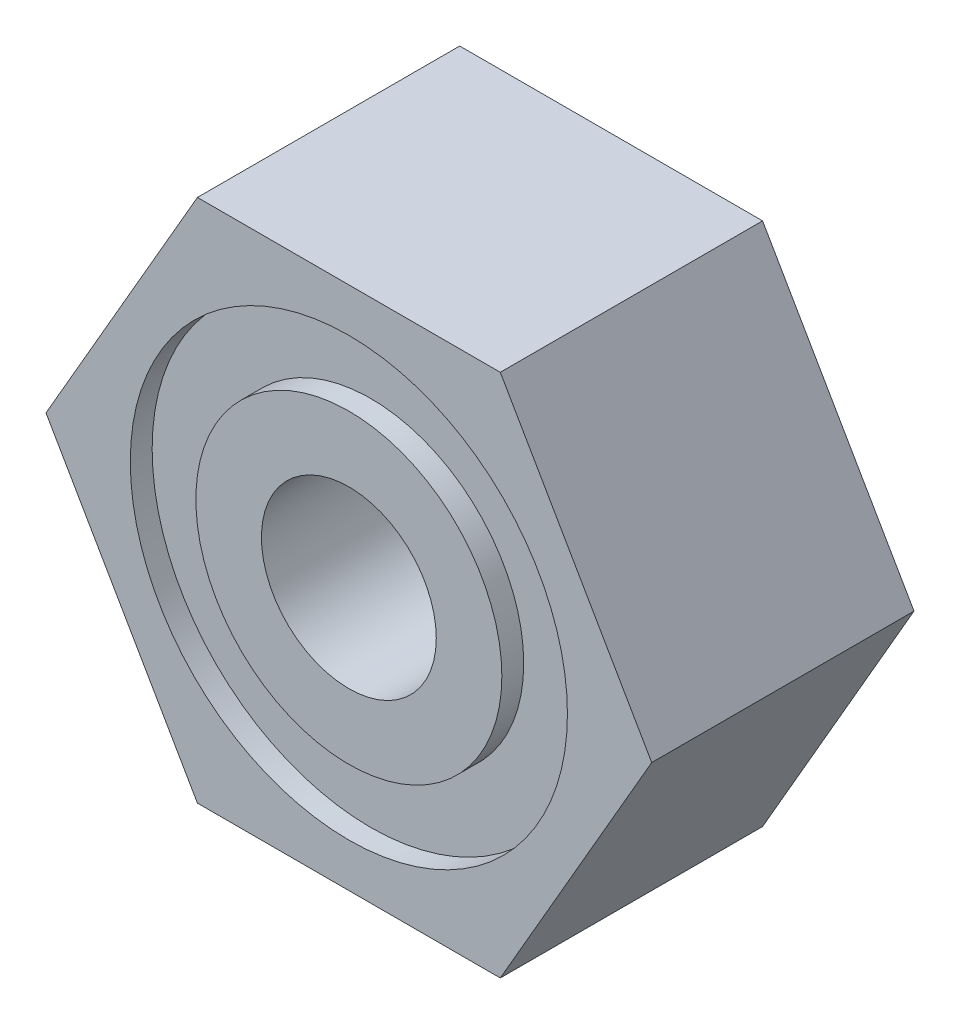
SolidWorks part; units mm, degrees
ref_plane "前视基准面" through (0, 0, 0) normal (0, 0, 1) x (1, 0, 0)
ref_plane "上视基准面" through (0, 0, 0) normal (0, 1, 0) x (1, 0, 0)
ref_plane "右视基准面" through (0, 0, 0) normal (1, 0, 0) x (0, 0, -1)
sketch "草图1" plane through (0, 0, 0) normal (0, 0, 1) x (1, 0, 0)
  line L1 (3.4641, -6) -> (6.9282, 0)
  line L2 (6.9282, 0) -> (3.4641, 6)
  line L3 (3.4641, 6) -> (-3.4641, 6)
  line L4 (-3.4641, 6) -> (-6.9282, 0)
  line L5 (-6.9282, 0) -> (-3.4641, -6)
  line L6 (-3.4641, -6) -> (3.4641, -6)
  circle A0 centre (0, 0) radius 6 construction
  circle A1 centre (0, 0) radius 2
  dimension "D2" = 4
  dimension "D1" = 12
extrude "凸台-拉伸1" add sketch "草图1" along normal blind 6
sketch "草图2" plane through (0, 0, 6) normal (0, 0, 1) x (1, 0, 0)
  circle A0 centre (0, 0) radius 5
  circle A1 centre (0, 0) radius 3.5
  dimension "D1" = 10
  dimension "D2" = 7
extrude "切除-拉伸1" cut sketch "草图2" against normal blind 0.5
ref_plane "基准面1" through (0, 0, 0) normal (0.5, -0.866, 0) x (-0.866, -0.5, 0)
sketch "草图3" plane through (0, 0, 0) normal (0.5, -0.866, 0) x (-0.866, -0.5, 0)
  circle A0 centre (0, 0) radius 1
  dimension "D1" = 2
extrude "切除-拉伸2" cut sketch "草图3" against normal mid plane 11
